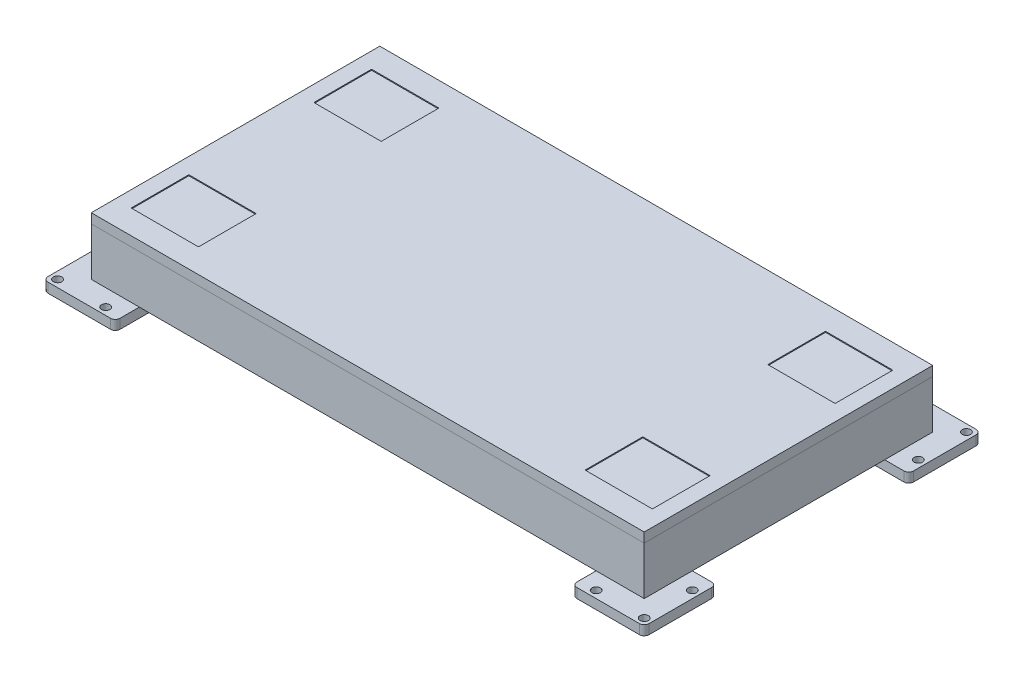
SolidWorks part; units mm, degrees
other "DetailItem1"
other "DetailItem2"
other "DetailItem3"
other "DetailItem4"
other "Weld Folder"
other "Weld Bead2"
other "Weld Bead3"
other "Weld Bead4"
other "Weld Bead1"
ref_plane "Front Plane" through (0, 0, 0) normal (0, 0, 1) x (1, 0, 0)
ref_plane "Top Plane" through (0, 0, 0) normal (0, 1, 0) x (1, 0, 0)
ref_plane "Right Plane" through (0, 0, 0) normal (1, 0, 0) x (0, 0, -1)
sketch "Sketch1" plane through (0, 0, 0) normal (0, 1, 0) x (1, 0, 0)
  line L1 (-575, -300) -> (575, -300)
  line L2 (-575, -300) -> (-575, 300)
  line L3 (-575, 300) -> (575, 300)
  line L4 (575, -300) -> (575, 300)
  line L5 (-575, -300) -> (575, 300) construction
  line L6 (-575, 300) -> (575, -300) construction
  point P0 (0, 0)
  dimension "D1" = 1150
  dimension "D2" = 600
other "C channel 100 X 10(2)"
ref_plane "Plane2" through (-575, 0, 300) normal (0, 0, -1) x (1, 0, 0)
sketch "Sketch12" plane through (-575, 0, 300) normal (0, 0, -1) x (1, 0, 0)
  line L0 (50, 100) -> (0, 100)
  line L1 (50, 0) -> (0, 0)
  line L2 (0, 100) -> (0, 0)
  line L6 (50, 100) -> (50, 98.3701)
  line L7 (50, 0) -> (50, 1.6299)
  line L12 (5.9, 82.48) -> (5.9, 17.52)
  line L17 (13.0638, 90.4362) -> (45.9704, 93.8948)
  line L18 (13.0638, 9.5638) -> (45.9704, 6.1052)
  arc A0 (45.9704, 93.8948) -> (50, 98.3701) centre (45.5, 98.3701) ccw
  arc A1 (45.9704, 6.1052) -> (50, 1.6299) centre (45.5, 1.6299) cw
  arc A9 (5.9, 17.52) -> (13.0638, 9.5638) centre (13.9, 17.52) ccw
  arc A10 (5.9, 82.48) -> (13.0638, 90.4362) centre (13.9, 82.48) cw
  point P8 (0, 50)
  point P9 (5.9, 50)
  point P10 (25, 100)
  point P11 (25, 0)
  point P12 (50, 5.6817)
  point P13 (50, 94.3183)
  point P14 (0, 0)
  dimension "D4" = 4.5
  dimension "RI" = 8
  dimension "D2" = 6
  dimension "D3" = 17.52
  dimension "Depth" = 100
  dimension "BF" = 50
  dimension "TW" = 5.9
  dimension "d1" = 64.96
sketch "Sketch13" plane through (0, 0, 0) normal (0, 1, 0) x (1, 0, 0)
  line L0 (-575, -300) -> (575, 300) construction
  line L1 (-575, -300) -> (575, -300)
  line L2 (-575, -300) -> (-575, 300)
  line L3 (-575, 300) -> (575, 300)
  line L4 (575, -300) -> (575, 300)
  line L5 (-575, -300) -> (575, 300) construction
  line L6 (-575, 300) -> (575, -300) construction
  point P0 (0, 0)
  point P9 (-575, -300)
  point P10 (-575, -296.0237)
  point P11 (575, -300)
  point P13 (572.9455, -300)
  point P14 (575, 297.4009)
  point P16 (573.1212, 299.0198)
  point P18 (-575, 300)
  point P19 (-573.2296, 299.0763)
  point P20 (0, 0)
  dimension "D1" = 600
extrude "Boss-Extrude1" add sketch "Sketch13" along normal blind 20 separate body
sketch "Sketch14" plane through (0, -100, 0) normal (0, -1, 0) x (1, 0, 0)
  line L0 (-525, 250) -> (-575, 300) construction
  line L1 (-615, 350) -> (-485, 350)
  line L2 (-625, 340) -> (-625, 210)
  line L3 (-615, 200) -> (-485, 200)
  line L4 (-475, 340) -> (-475, 210)
  line L5 (-625, 350) -> (-475, 200) construction
  line L6 (-625, 200) -> (-475, 350) construction
  line L7 (-575, 300) -> (575, 300) construction
  line L8 (-575, 300) -> (-575, -300) construction
  line L9 (0, 0) -> (0, 300) construction
  line L10 (625, 200) -> (475, 350) construction
  line L11 (625, 350) -> (475, 200) construction
  line L12 (475, 340) -> (475, 210)
  line L13 (615, 200) -> (485, 200)
  line L14 (625, 340) -> (625, 210)
  line L15 (615, 350) -> (485, 350)
  line L16 (-575, 0) -> (0, 0) construction
  line L17 (625, -350) -> (475, -200) construction
  line L18 (625, -200) -> (475, -350) construction
  line L19 (615, -350) -> (485, -350)
  line L20 (625, -340) -> (625, -210)
  line L21 (615, -200) -> (485, -200)
  line L22 (475, -340) -> (475, -210)
  line L23 (-625, -200) -> (-475, -350) construction
  line L24 (-625, -350) -> (-475, -200) construction
  line L25 (-475, -340) -> (-475, -210)
  line L26 (-615, -200) -> (-485, -200)
  line L27 (-625, -340) -> (-625, -210)
  line L28 (-615, -350) -> (-485, -350)
  arc A0 (-625, 210) -> (-615, 200) centre (-615, 210) ccw
  arc A1 (-485, 200) -> (-475, 210) centre (-485, 210) ccw
  arc A2 (-485, 350) -> (-475, 340) centre (-485, 340) cw
  arc A3 (-615, 350) -> (-625, 340) centre (-615, 340) ccw
  circle A4 centre (-510, 335) radius 8.75
  circle A5 centre (-610, 335) radius 8.75
  circle A6 centre (-610, 235) radius 8.75
  circle A7 centre (610, 235) radius 8.75
  circle A8 centre (610, 335) radius 8.75
  circle A9 centre (510, 335) radius 8.75
  arc A10 (615, 350) -> (625, 340) centre (615, 340) cw
  arc A11 (485, 350) -> (475, 340) centre (485, 340) ccw
  arc A12 (485, 200) -> (475, 210) centre (485, 210) cw
  arc A13 (625, 210) -> (615, 200) centre (615, 210) cw
  arc A14 (625, -210) -> (615, -200) centre (615, -210) ccw
  arc A15 (485, -200) -> (475, -210) centre (485, -210) ccw
  arc A16 (485, -350) -> (475, -340) centre (485, -340) cw
  arc A17 (615, -350) -> (625, -340) centre (615, -340) ccw
  circle A18 centre (510, -335) radius 8.75
  circle A19 centre (610, -335) radius 8.75
  circle A20 centre (610, -235) radius 8.75
  circle A21 centre (-610, -235) radius 8.75
  circle A22 centre (-610, -335) radius 8.75
  circle A23 centre (-510, -335) radius 8.75
  arc A24 (-615, -350) -> (-625, -340) centre (-615, -340) cw
  arc A25 (-485, -350) -> (-475, -340) centre (-485, -340) ccw
  arc A26 (-485, -200) -> (-475, -210) centre (-485, -210) cw
  arc A27 (-625, -210) -> (-615, -200) centre (-615, -210) cw
  point P0 (-550, 275)
  point P54 (550, 275)
  point P78 (550, -275)
  point P101 (-550, -275)
  dimension "D3" = 10
  dimension "D6" = 17.5
  dimension "D1" = 50
  dimension "D2" = 50
  dimension "D4" = 15
  dimension "D5" = 15
  dimension "D7" = 100
  dimension "D8" = 100
extrude "Boss-Extrude2" add sketch "Sketch14" along normal blind 20 separate body
sketch "Sketch15" plane through (0, 20, 0) normal (0, 1, 0) x (1, 0, 0)
  line L1 (-542, 250) -> (-402, 250)
  line L2 (-542, 250) -> (-542, 130)
  line L3 (-542, 130) -> (-402, 130)
  line L4 (-402, 250) -> (-402, 130)
  dimension "D1" = 120
  dimension "D2" = 140
  dimension "D3" = 402
  dimension "D4" = 130
extrude "Cut-Extrude1" cut sketch "Sketch15" against normal blind 2
mirror "Mirror1" about plane through (0, 0, 0) normal (1, 0, 0) of "Cut-Extrude1"
mirror "Mirror2" about plane through (0, 0, 0) normal (0, 0, 1) of "Mirror1", "Cut-Extrude1"
